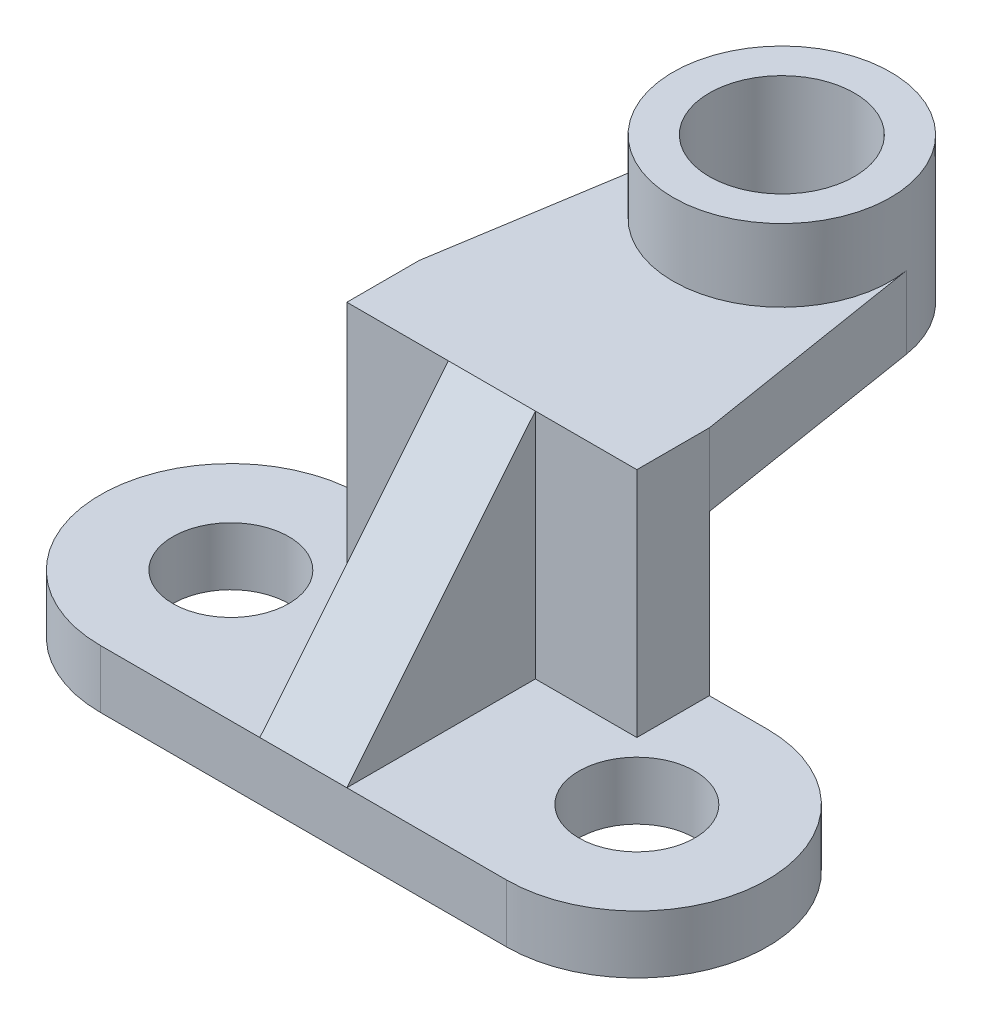
SolidWorks part; units mm, degrees
ref_plane "Front Plane" through (0, 0, 0) normal (0, 0, 1) x (1, 0, 0)
ref_plane "Top Plane" through (0, 0, 0) normal (0, 1, 0) x (1, 0, 0)
ref_plane "Right Plane" through (0, 0, 0) normal (1, 0, 0) x (0, 0, -1)
sketch "Sketch2" plane through (0, 0, 0) normal (0, 1, 0) x (1, 0, 0)
  line L1 (-28, 18) -> (28, 18)
  line L2 (-28, 18) -> (-28, -18) construction
  line L3 (-28, -18) -> (28, -18)
  line L4 (28, 18) -> (28, -18) construction
  line L5 (-28, 18) -> (28, -18) construction
  line L6 (-28, -18) -> (28, 18) construction
  arc A0 (-28, -18) -> (-28, 18) centre (-28, 0) cw
  arc A1 (28, 18) -> (28, -18) centre (28, 0) cw
  circle A2 centre (-28, 0) radius 8
  circle A3 centre (28, 0) radius 8
  point P0 (0, 0)
  dimension "D3" = 16
  dimension "D4" = 16
  dimension "D1" = 36
  dimension "D2" = 56
extrude "Boss-Extrude1" add sketch "Sketch2" along normal blind 8
sketch "Sketch4" plane through (0, 8, 0) normal (0, 1, 0) x (1, 0, 0)
  line L0 (28, 18) -> (-28, 18) construction
  line L1 (-20, 18) -> (20, 18)
  line L2 (0, 18) -> (0, 8) construction
  line L3 (-20, 8) -> (20, 8)
  line L4 (20, 18) -> (20, 8)
  line L5 (-20, 18) -> (-20, 8)
  dimension "D1" = 20
  dimension "D2" = 10
extrude "Boss-Extrude2" add sketch "Sketch4" along normal blind 32
sketch "Sketch5" plane through (0, 0, 0) normal (1, 0, 0) x (0, 0, -1)
  line L0 (8, 40) -> (8, 8)
  line L1 (18, 8) -> (-18, 8) construction
  line L2 (8, 40) -> (8, 8) construction
  line L3 (8, 8) -> (-18, 8)
  line L4 (-18, 8) -> (8, 40)
extrude "Boss-Extrude3" add sketch "Sketch5" along normal blind 6 and the other way blind 6
sketch "Sketch7" plane through (0, 40, 0) normal (0, 1, 0) x (1, 0, 0)
  line L0 (0, -19.8) -> (0, 19.8) construction
  line L1 (20, 18) -> (-20, 18) construction
  line L2 (-20, 18) -> (-14.811, 50.374)
  line L3 (20, 18) -> (14.811, 50.374)
  arc A0 (14.811, 50.374) -> (-14.811, 50.374) centre (0, 48) ccw
  circle A1 centre (0, 48) radius 10
  line M4 (20, 18) -> (-20, 18)
  dimension "D1" = 20
  dimension "D2" = 30
  dimension "D3" = 30
extrude "Boss-Extrude4" add sketch "Sketch7" against normal blind 10 contours L3 A0 L2 A1 M4
sketch "Sketch8" plane through (0, 40, 0) normal (0, 1, 0) x (1, 0, 0)
  circle A0 centre (0, 48) radius 10 construction
  circle A1 centre (0, 48) radius 10
  circle A2 centre (0, 48) radius 15
extrude "Boss-Extrude5" add sketch "Sketch8" along normal blind 10
